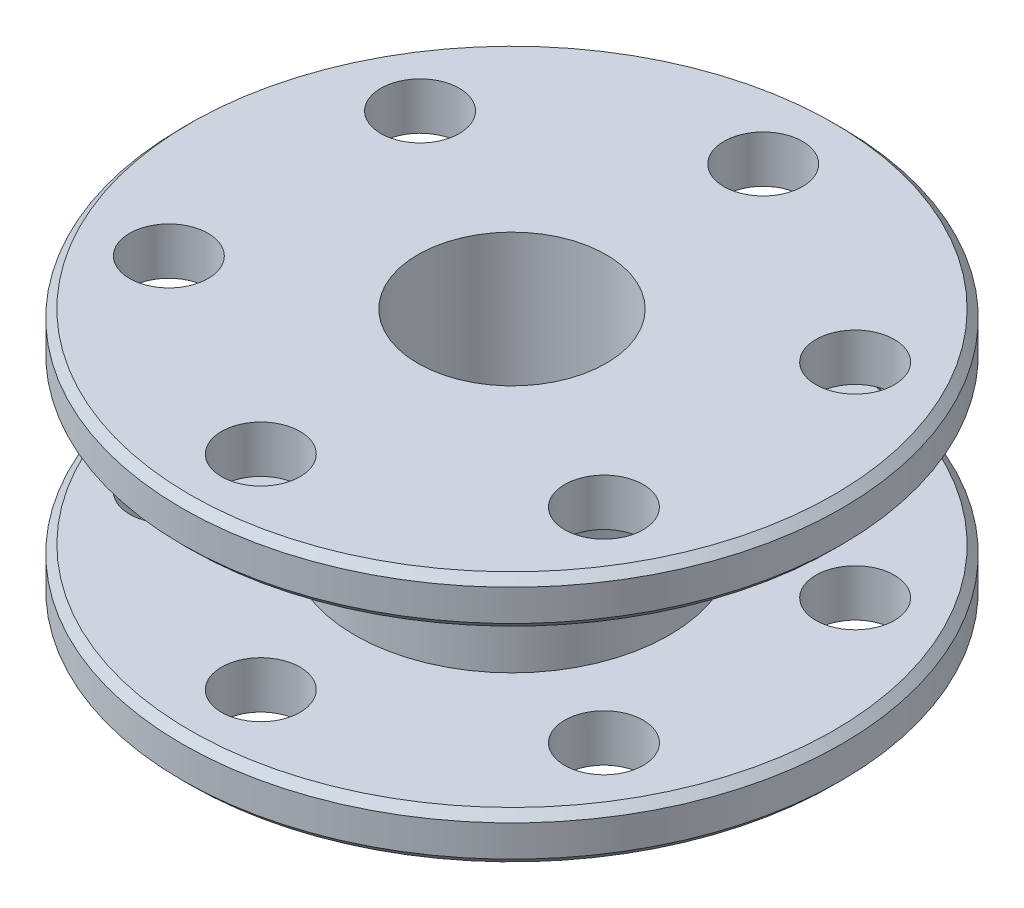
SolidWorks part; units mm, degrees
ref_plane "Front Plane" through (0, 0, 0) normal (0, 0, 1) x (1, 0, 0)
ref_plane "Top Plane" through (0, 0, 0) normal (0, 1, 0) x (1, 0, 0)
ref_plane "Right Plane" through (0, 0, 0) normal (1, 0, 0) x (0, 0, -1)
sketch "Sketch1" plane through (0, 0, 0) normal (0, 1, 0) x (1, 0, 0)
  circle A0 centre (0, 0) radius 6
  circle A1 centre (0, 0) radius 21
  circle A2 centre (0, 0) radius 16 construction
  circle A3 centre (0, 16) radius 2.5
  circle A4 centre (13.8564, 8) radius 2.5
  circle A5 centre (13.8564, -8) radius 2.5
  circle A6 centre (0, -16) radius 2.5
  circle A7 centre (-13.8564, -8) radius 2.5
  circle A8 centre (-13.8564, 8) radius 2.5
  point P19 (0, 0)
  dimension "D1" = 42
  dimension "D2" = 12
  dimension "D3" = 32
  dimension "D4" = 5
  dimension "D5" = 6
extrude "Boss-Extrude1" add sketch "Sketch1" along normal blind 16
sketch "Sketch2" plane through (0, 0, 0) normal (1, 0, 0) x (0, 0, -1)
  line L0 (0, 0) -> (0, 21.0727) construction
  line L1 (18.5, 16) -> (13.5, 16) construction
  line L2 (10, 13) -> (27.3377, 13)
  line L3 (10, 13) -> (10, 3)
  line L4 (10, 3) -> (27.3377, 3)
  line L5 (27.3377, 13) -> (27.3377, 3)
  line L6 (-21, 0) -> (21, 0) construction
  dimension "D1" = 3
  dimension "D2" = 3
  dimension "D3" = 10
revolve "Cut-Revolve1" cut sketch "Sketch2" angle 360 about L0
chamfer "Chamfer1" distance 0.5 angle 45 4 edges at (0, 0, 21) (0, 3, -21) (0, 16, 21) (0, 13, 21)
